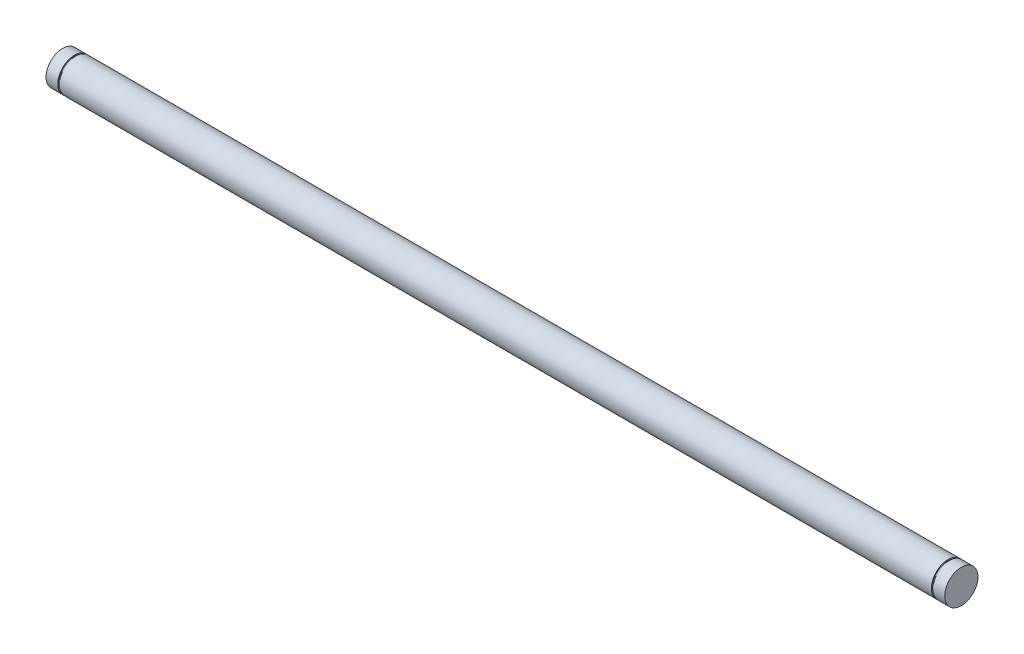
SolidWorks part; units mm, degrees
ref_plane "Front Plane" through (0, 0, 0) normal (0, 0, 1) x (1, 0, 0)
ref_plane "Top Plane" through (0, 0, 0) normal (0, 1, 0) x (1, 0, 0)
ref_plane "Right Plane" through (0, 0, 0) normal (1, 0, 0) x (0, 0, -1)
sketch "Sketch1" plane through (0, 0, 0) normal (1, 0, 0) x (0, 0, -1)
  circle A0 centre (0, 0) radius 12.7
  dimension "D1" = 25.4
extrude "Boss-Extrude1" add sketch "Sketch1" along normal blind 685.8
ref_plane "Plane1" through (342.9, 0, 0) normal (-1, 0, 0) x (0, 0, 1)
ref_plane "Plane2" through (10.16, 0, 0) normal (-1, 0, 0) x (0, 0, 1)
sketch "Sketch2" plane through (10.16, 0, 0) normal (-1, 0, 0) x (0, 0, 1)
  circle A0 centre (0, 0) radius 11.938
  circle A1 centre (0, 0) radius 12.7
  circle A2 centre (0, 0) radius 12.7 construction
  dimension "D1" = 23.876
extrude "Cut-Extrude1" cut sketch "Sketch2" along normal blind 1.1684
mirror "Mirror1" about plane through (342.9, 0, 0) normal (-1, 0, 0) of "Cut-Extrude1"
